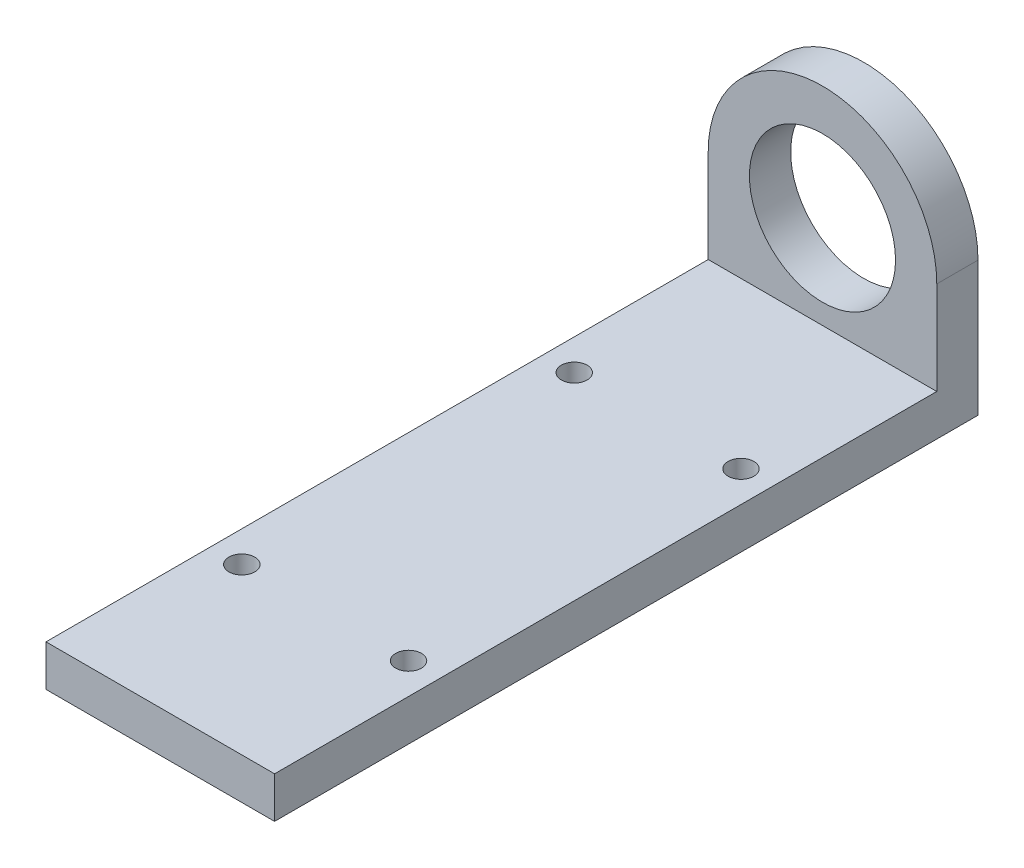
SolidWorks part; units mm, degrees
ref_plane "Front Plane" through (0, 0, 0) normal (0, 0, 1) x (1, 0, 0)
ref_plane "Top Plane" through (0, 0, 0) normal (0, 1, 0) x (1, 0, 0)
ref_plane "Right Plane" through (0, 0, 0) normal (1, 0, 0) x (0, 0, -1)
sketch "Sketch1" plane through (0, 0, 0) normal (0, 0, 1) x (1, 0, 0)
  line L0 (-17.604, 0) -> (-17.604, -20.7)
  line L1 (-17.604, -20.7) -> (17.604, -20.7)
  line L2 (17.604, -20.7) -> (17.604, 0)
  circle A0 centre (0, 0) radius 11 construction
  arc A1 (17.604, 0) -> (-17.604, 0) centre (0, 0) ccw
  circle A2 centre (0, 0) radius 11 construction
  circle A3 centre (0, 0) radius 11.254
  point P12 (17.604, -20.7)
  dimension "D2" = 6.35
  dimension "D3" = 20.7
  dimension "D1" = 0.254
extrude "Boss-Extrude1" add sketch "Sketch1" along normal blind 6.35
sketch "Sketch2" plane through (0, 0, 6.35) normal (0, 0, 1) x (1, 0, 0)
  line L0 (-17.604, 0) -> (-17.604, -20.7) construction
  line L1 (-17.604, -20.7) -> (17.604, -20.7)
  line L2 (-17.604, -20.7) -> (-17.604, -14.35)
  line L3 (-17.604, -14.35) -> (17.604, -14.35)
  line L4 (17.604, -20.7) -> (17.604, -14.35)
  line L5 (-17.604, -20.7) -> (17.604, -20.7) construction
  line L6 (17.604, -20.7) -> (17.604, 0) construction
  dimension "D1" = 6.35
extrude "Boss-Extrude2" add sketch "Sketch2" along normal up to surface (102 mm away)
sketch "Sketch3" plane through (0, -14.35, 0) normal (0, 1, 0) x (1, 0, 0)
  line L0 (0, -108.35) -> (0, -6.35) construction
  line L1 (17.604, -108.35) -> (-17.604, -108.35) construction
  line L2 (-17.604, -6.35) -> (17.604, -6.35) construction
  line L3 (12.8415, -6.35) -> (12.8415, -108.35) construction
  line L4 (17.604, -108.35) -> (17.604, -6.35) construction
  line L6 (0, -79.4939) -> (17.604, -79.4939) construction
  line L7 (17.604, -6.35) -> (-17.604, -6.35) construction
  circle A0 centre (12.8415, -31.75) radius 1.9844
  circle A1 centre (12.8415, -82.95) radius 1.9844
  circle A2 centre (-12.8415, -82.95) radius 1.9844
  circle A3 centre (-12.8415, -31.75) radius 1.9844
  point P23 (0, 0)
  dimension "D1" = 3.9688
  dimension "D2" = 25.4
  dimension "D3" = 25.4
  dimension "D4" = 4.7625
extrude "Cut-Extrude1" cut sketch "Sketch3" against normal through all
